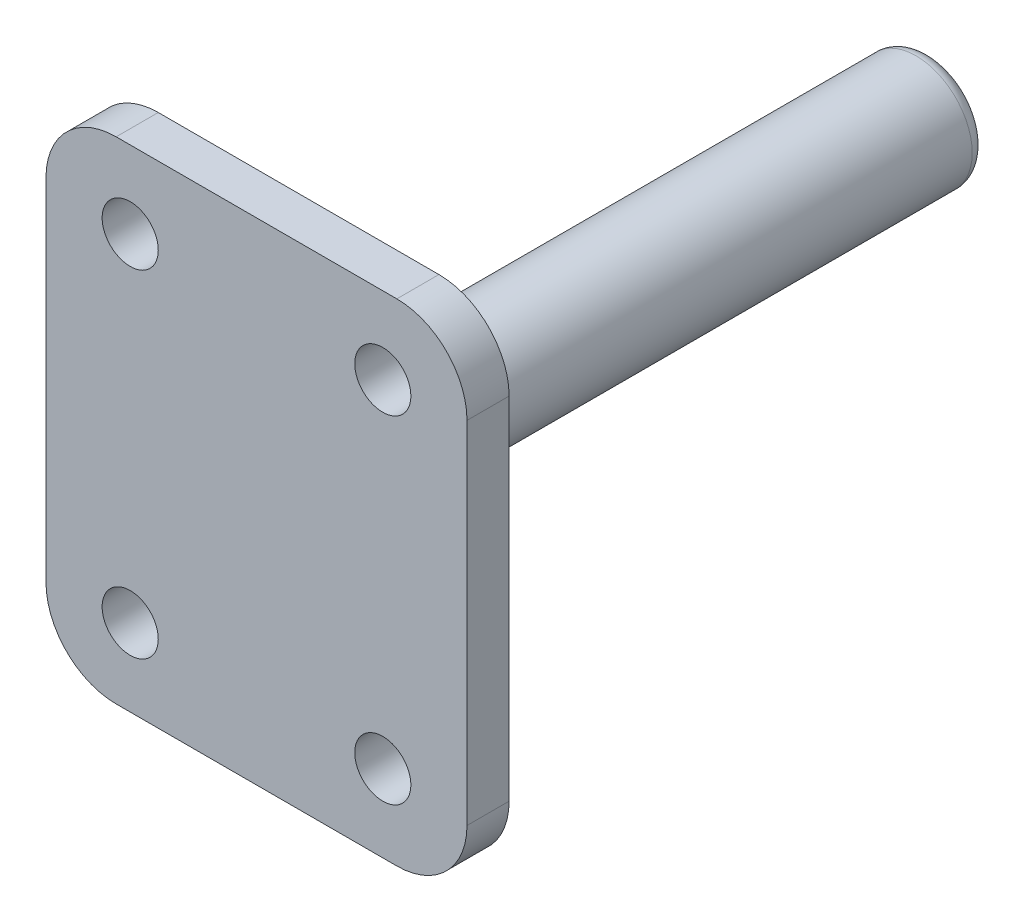
SolidWorks part; units mm, degrees
material "Plain Carbon Steel"
ref_plane "Front Plane" through (0, 0, 0) normal (0, 0, 1) x (1, 0, 0)
ref_plane "Top Plane" through (0, 0, 0) normal (0, 1, 0) x (1, 0, 0)
ref_plane "Right Plane" through (0, 0, 0) normal (1, 0, 0) x (0, 0, -1)
sketch "Sketch2" plane through (0, 0, 0) normal (0, 0, 1) x (1, 0, 0)
  line L0 (0, 0) -> (30, 0)
  line L1 (0, 0) -> (0, -35)
  line L2 (30, 0) -> (30, -35)
  line L3 (0, -35) -> (30, -35)
  line L4 (0, -17.5) -> (30, -17.5) construction
  line L5 (15, 0) -> (15, -35) construction
  dimension "D1" = 30
  dimension "D2" = 35
extrude "Boss-Extrude1" add sketch "Sketch2" along normal blind 3
fillet "Fillet1" radius 5 4 edges at (0, -35, 1.5) (30, -35, 1.5) (30, 0, 1.5) (0, 0, 1.5)
sketch "Sketch3" plane through (0, 0, 3) normal (0, 0, 1) x (1, 0, 0)
  line L0 (0, -17.5) -> (30, -17.5) construction
  line L1 (0, -5) -> (0, -30) construction
  line L2 (30, -30) -> (30, -5) construction
  line L4 (6, -5.5) -> (24, -5.5) construction
  line L5 (6, -5.5) -> (6, -29.5) construction
  line L6 (24, -5.5) -> (24, -29.5) construction
  line L7 (6, -29.5) -> (24, -29.5) construction
  circle A4 centre (6, -5.5) radius 2
  circle A5 centre (24, -5.5) radius 2
  circle A6 centre (6, -29.5) radius 2
  circle A7 centre (24, -29.5) radius 2
  point P2 (15, -5.5)
  point P5 (15, -17.5)
  point P16 (30, -17.5)
  point P17 (24, -17.5)
  dimension "D1" = 4
  dimension "D2" = 24
  dimension "D3" = 18
extrude "Cut-Extrude1" cut sketch "Sketch3" against normal blind 10
sketch "Sketch6" plane through (0, 0, 0) normal (0, 0, -1) x (-1, 0, 0)
  line L0 (-30, -17.5) -> (0, -17.5) construction
  line L1 (-30, -30) -> (-30, -5) construction
  line L3 (0, -5) -> (0, -30) construction
  circle A0 centre (-15, -17.5) radius 4
  point P2 (-15, -17.5)
  dimension "D1" = 8
extrude "Boss-Extrude2" add sketch "Sketch6" along normal blind 45
fillet "Fillet2" radius 1 1 edges at (11, -17.5, -45)
